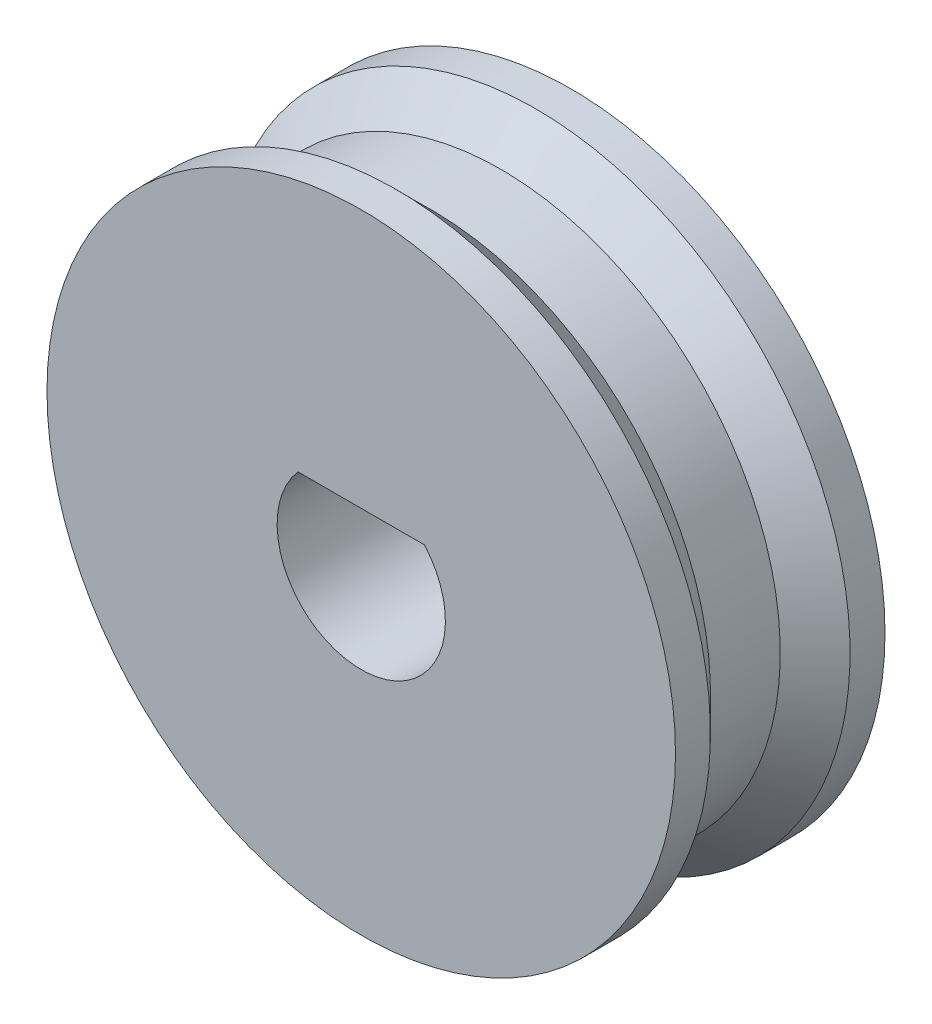
SolidWorks part; units mm, degrees
ref_plane "Front Plane" through (0, 0, 0) normal (0, 0, 1) x (1, 0, 0)
ref_plane "Top Plane" through (0, 0, 0) normal (0, 1, 0) x (1, 0, 0)
ref_plane "Right Plane" through (0, 0, 0) normal (1, 0, 0) x (0, 0, -1)
sketch "Sketch1" plane through (0, 0, 0) normal (0, 0, 1) x (1, 0, 0)
  circle A0 centre (0, 0) radius 4.5
  dimension "D1" = 9
extrude "main_base" add sketch "Sketch1" along normal blind 3
sketch "Sketch2" plane through (0, 0, 0) normal (1, 0, 0) x (0, 0, -1)
  line L0 (-2.5, 4.5) -> (-0.5, 4.5)
  line L1 (0, 4.5) -> (-3, 4.5) construction
  line L2 (-2.5, 4.5) -> (-2, 4)
  line L3 (-2, 4) -> (-1, 4)
  line L4 (-1, 4) -> (-0.5, 4.5)
  line L5 (-3, 4.5) -> (-3, -4.5) construction
  line L6 (0, -4.5) -> (0, 4.5) construction
  line L7 (0, 0) -> (-3, 0) construction
  point P13 (-1.5, 4.5)
  point P14 (-1.5, 4)
  dimension "D1" = 0.5
  dimension "D2" = 0.5
  dimension "D3" = 45
  dimension "D4" = 1
revolve "pulley_cut_out" cut sketch "Sketch2" angle 360 about L7
sketch "Sketch3" plane through (0, 0, 0) normal (0, 0, 1) x (1, 0, 0)
  line L0 (0.9055, 0.795) -> (-0.9055, 0.795)
  line L1 (4.3357, -1.205) -> (-4.3357, -1.205) construction
  circle A0 centre (0, 0) radius 1.205
  point P10 (0, -1.205)
  dimension "D1" = 2.41
  dimension "D2" = 2
extrude "motor_shaft_cut_out" cut sketch "Sketch3" along normal through all contours L0 A0
